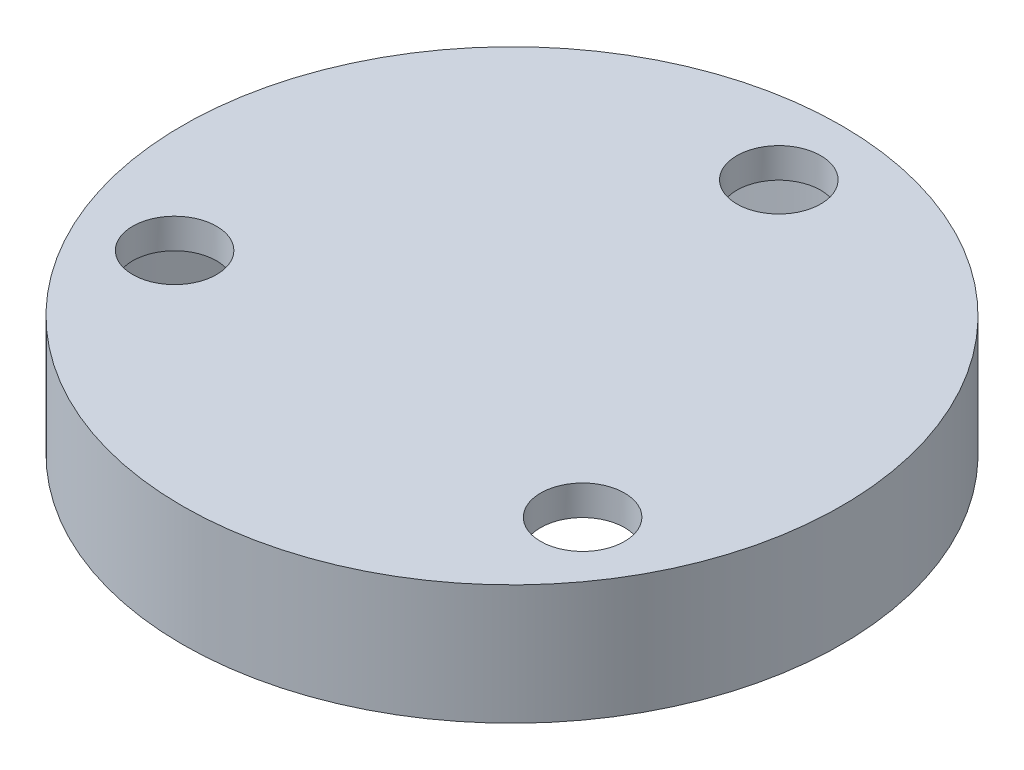
SolidWorks part; units mm, degrees
ref_plane "Front Plane" through (0, 0, 0) normal (0, 0, 1) x (1, 0, 0)
ref_plane "Top Plane" through (0, 0, 0) normal (0, 1, 0) x (1, 0, 0)
ref_plane "Right Plane" through (0, 0, 0) normal (1, 0, 0) x (0, 0, -1)
sketch "Sketch1" plane through (0, 0, 0) normal (0, 1, 0) x (1, 0, 0)
  circle A0 centre (0, 0) radius 55
  dimension "D1" = 110
extrude "Boss-Extrude1" add sketch "Sketch1" along normal blind 20
sketch "Sketch2" plane through (0, 0, 0) normal (0, -1, 0) x (1, 0, 0)
  circle A0 centre (0, 0) radius 50
  dimension "D1" = 100
extrude "Cut-Extrude1" cut sketch "Sketch2" against normal blind 15
hole_wizard "Ø1.0mm Dowel Hole1" positions "Sketch3" profile "Sketch4" hole size "Ø1.0" standard "ANSI Metric" end condition through all
sketch "Sketch3" plane through (0, 20, 0) normal (0, 1, 0) x (1, 0, 0)
  line L0 (0, 0) -> (34.9996, -23.217) construction
  line L3 (0, 0) -> (2.6067, 41.919) construction
  line L6 (0, 0) -> (-37.6063, -18.7021) construction
  circle A0 centre (0, 0) radius 42 construction
  point P0 (34.9996, -23.217)
  point P2 (2.6067, 41.919)
  point P4 (-37.6063, -18.7021)
  dimension "D3" = 84
  dimension "D1" = 120
  dimension "D2" = 120
sketch "Sketch4" plane through (34.9996, 20, 23.217) normal (1, 0, 0) x (0, 0, 1)
  line L0 (0, 0) -> (0, 20)
  line L1 (0, 20) -> (7, 20)
  line L2 (7, 20) -> (7, 0)
  line L5 (7, 0) -> (0, 0)
  line L11 (0, -6.35) -> (0, 107.95) construction
  dimension "Thru Hole Dia." = 14
  dimension "Thru Hole Depth" = 20
